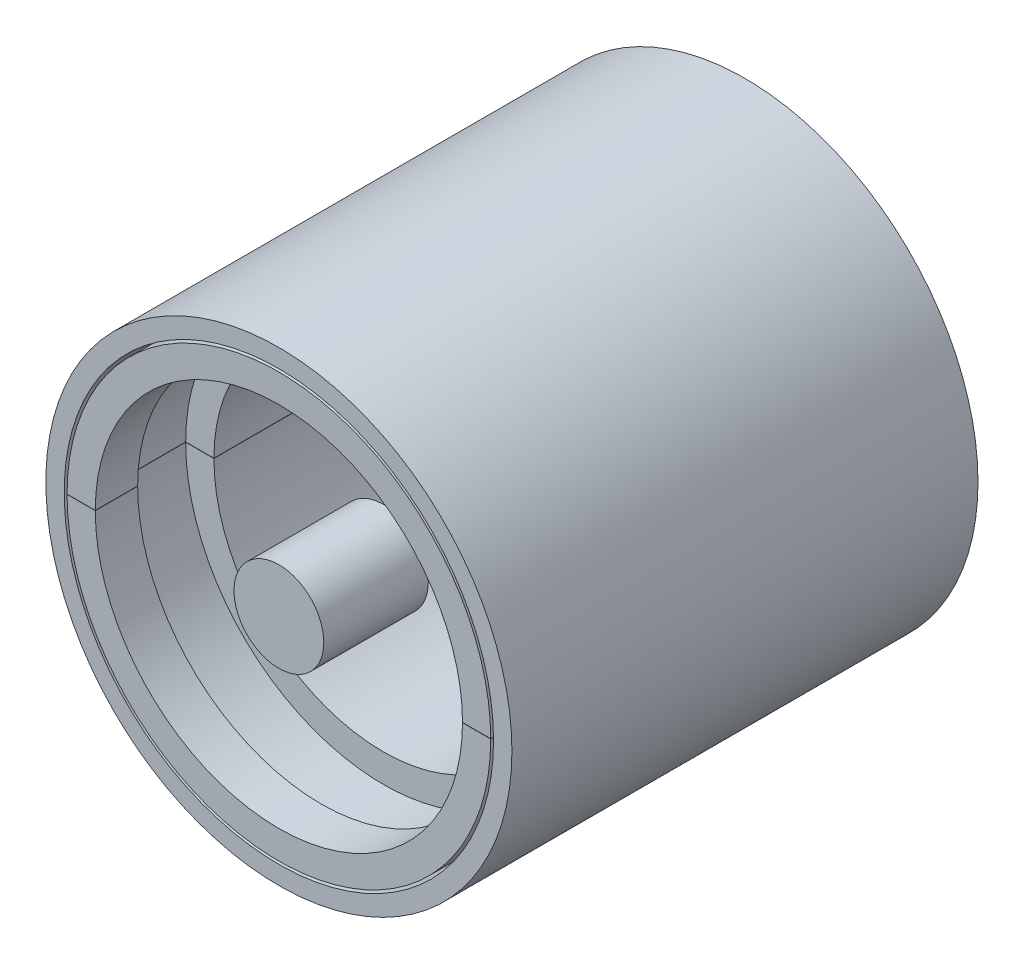
SolidWorks part; units mm, degrees
other "sleeve"
ref_plane "Front Plane" through (0, 0, 0) normal (0, 0, 1) x (1, 0, 0)
ref_plane "Top Plane" through (0, 0, 0) normal (0, 1, 0) x (1, 0, 0)
ref_plane "Right Plane" through (0, 0, 0) normal (1, 0, 0) x (0, 0, -1)
sketch "Sketch1" plane through (0, 0, 0) normal (0, 0, 1) x (1, 0, 0)
  circle A0 centre (0, 0) radius 6.5
  circle A1 centre (0, 0) radius 7.5
  dimension "D1" = 13
  dimension "D2" = 15
extrude "Boss-Extrude1" add sketch "Sketch1" along normal blind 1.5
sketch "Sketch2" plane through (0, 0, 0) normal (0, 0, -1) x (-1, 0, 0)
  circle A0 centre (0, 0) radius 7.5
  circle A1 centre (0, 0) radius 7
  circle A2 centre (0, 0) radius 7.5 construction
  dimension "D1" = 0.5
extrude "Boss-Extrude2" add sketch "Sketch2" along normal blind 8
sketch "Sketch3" plane through (0, 0, -8) normal (0, 0, -1) x (-1, 0, 0)
  line L0 (0, 0) -> (-10.0206, 0) construction
  line L2 (-7.0725, 0) -> (-3.5363, -6.125)
  line L3 (-3.5363, -6.125) -> (3.5363, -6.125)
  line L4 (3.5363, -6.125) -> (7.0725, 0)
  line L5 (7.0725, 0) -> (3.5363, 6.125)
  line L6 (3.5363, 6.125) -> (-3.5363, 6.125)
  line L7 (-3.5363, 6.125) -> (-7.0725, 0)
  circle A0 centre (0, 0) radius 6.125 construction
  circle A1 centre (0, 0) radius 7.5
  circle A2 centre (0, 0) radius 7.5 construction
  dimension "D1" = 12.25
extrude "Boss-Extrude3" add sketch "Sketch3" along normal blind 4.75
sketch "Sketch4" plane through (0, 0, -12.75) normal (0, 0, -1) x (-1, 0, 0)
  circle A0 centre (0, 0) radius 5
  circle A1 centre (0, 0) radius 7.5
  circle A2 centre (0, 0) radius 7.5 construction
  dimension "D1" = 10
extrude "Boss-Extrude4" add sketch "Sketch4" along normal blind 1.25
sketch "Sketch5" plane through (0, 0, 1.5) normal (0, 0, 1) x (1, 0, 0)
  line L1 (8.7868, 0) -> (-9.3688, 0) construction
  line L2 (-8.571, 0.005) -> (8.2262, 0.005)
  line L3 (-8.571, 0.005) -> (-8.571, -0.005)
  line L4 (-8.571, -0.005) -> (8.2262, -0.005)
  line L5 (8.2262, 0.005) -> (8.2262, -0.005)
  point P7 (-8.571, 0)
  dimension "D1" = 0.01
extrude "Cut-Extrude1" cut sketch "Sketch5" against normal up to surface (15.5 mm away) contours L3 L2 L5 L4 up to face at (-7.5, 0, -14)
sketch "Sketch6" plane through (0, 0, -14) normal (0, 0, -1) x (-1, 0, 0)
  circle A0 centre (0, 0) radius 8.25
  arc A1 (7.5, 0.005) -> (-7.5, 0.005) centre (0, 0) ccw construction
  dimension "D1" = 0.75
extrude "Boss-Extrude5" add sketch "Sketch6" along normal blind 1 separate body
sketch "Sketch7" plane through (0, 0, -14) normal (0, 0, 1) x (1, 0, 0)
  circle A0 centre (0, 0) radius 7.6
  circle A1 centre (0, 0) radius 8.25
  circle A2 centre (0, 0) radius 8.25 construction
  arc A3 (7.5, 0.005) -> (-7.5, 0.005) centre (0, 0) ccw construction
  dimension "D1" = 0.1
extrude "Boss-Extrude6" add sketch "Sketch7" along normal blind 15.5
sketch "Sketch8" plane through (0, 0, -15) normal (0, 0, -1) x (-1, 0, 0)
  circle A0 centre (0, 0) radius 7.25
  circle A1 centre (0, 0) radius 8.25 construction
  dimension "D1" = 1
extrude "Cut-Extrude2" cut sketch "Sketch8" against normal up to surface (16.5 mm away) up to face at (8.25, 0, 1.5)
sketch "Sketch11" plane through (0, 0, 1.5) normal (0, 0, 1) x (1, 0, 0)
  circle A0 centre (0, 0) radius 1.5898
extrude "Boss-Extrude8" add sketch "Sketch11" against normal blind 3.7 separate body
sketch "Sketch12" plane through (0, 0, -2.2) normal (0, 0, -1) x (-1, 0, 0)
  line L1 (-8.2262, 0.005) -> (8.571, 0.005)
  line L2 (-8.2262, 0.005) -> (-8.2262, -0.005)
  line L3 (-8.2262, -0.005) -> (8.571, -0.005)
  line L4 (8.571, 0.005) -> (8.571, -0.005)
  circle A0 centre (0, 0) radius 6
  circle A1 centre (0, 0) radius 7.5
  arc A2 (7.5, 0.005) -> (-7.5, 0.005) centre (0, 0) ccw construction
  dimension "D1" = 12
extrude "Boss-Extrude10" add sketch "Sketch12" along normal up to surface (5.8 mm away) contours L1 A1 A0 | L3 A1 A0 up to face at (0, 6.5625, -8)
